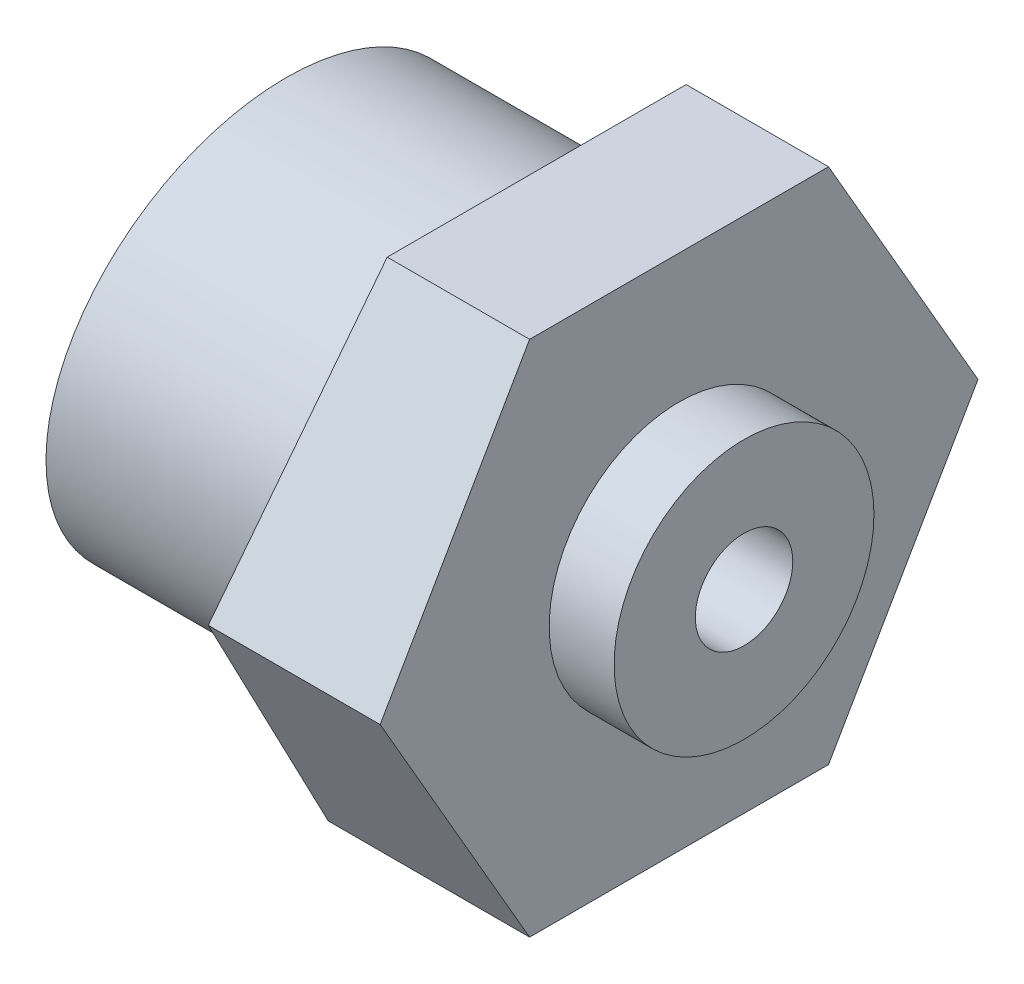
SolidWorks part; units mm, degrees
ref_plane "Front Plane" through (0, 0, 0) normal (0, 0, 1) x (1, 0, 0)
ref_plane "Top Plane" through (0, 0, 0) normal (0, 1, 0) x (1, 0, 0)
ref_plane "Right Plane" through (0, 0, 0) normal (1, 0, 0) x (0, 0, -1)
sketch "Croquis1" plane through (0, 0, 0) normal (1, 0, 0) x (0, 0, -1)
  line L1 (-4.6015, 0) -> (-2.3007, -3.985)
  line L2 (-2.3007, -3.985) -> (2.3007, -3.985)
  line L3 (2.3007, -3.985) -> (4.6015, 0)
  line L4 (4.6015, 0) -> (2.3007, 3.985)
  line L5 (2.3007, 3.985) -> (-2.3007, 3.985)
  line L6 (-2.3007, 3.985) -> (-4.6015, 0)
  circle A0 centre (0, 0) radius 3.985 construction
  dimension "D1" = 7.97
extrude "Saliente-Extruir1" add sketch "Croquis1" against normal blind 3.1
sketch "Croquis2" plane through (0, 0, 0) normal (0, 0, 1) x (1, 0, 0)
  line L0 (-3.1, -3.985) -> (-2.1919, 3.985)
  line L1 (-3.1, 3.985) -> (0, 3.985) construction
  line L2 (-2.1919, 3.985) -> (-3.5279, 3.985)
  line L3 (-3.5279, 3.985) -> (-3.1, -3.985)
  dimension "D1" = 83.5
extrude "Cortar-Extruir1" cut sketch "Croquis2" against normal mid plane 33
sketch "Croquis3" plane through (0, 0, 0) normal (1, 0, 0) x (0, 0, -1)
  circle A0 centre (0, 0) radius 3.3
  dimension "D1" = 6.6
extrude "Saliente-Extruir2" add sketch "Croquis3" against normal blind 6.8
sketch "Croquis4" plane through (0, 0, 0) normal (0, 0, 1) x (1, 0, 0)
  line L0 (-6.8, -3.3) -> (-6.048, 3.3)
  line L1 (-2.27, 3.3) -> (-6.8, 3.3) construction
  line L2 (-6.048, 3.3) -> (-6.8, 3.3)
  line L3 (-6.8, 3.3) -> (-6.8, -3.3)
  dimension "D1" = 83.5
extrude "Cortar-Extruir2" cut sketch "Croquis4" against normal mid plane 6.8
sketch "Croquis5" plane through (0, 0, 0) normal (1, 0, 0) x (0, 0, -1)
  circle A0 centre (0, 0) radius 2
  dimension "D1" = 4
extrude "Saliente-Extruir3" add sketch "Croquis5" along normal blind 1
sketch "Croquis6" plane through (1, 0, 0) normal (1, 0, 0) x (0, 0, -1)
  circle A0 centre (0, 0) radius 0.75
  dimension "D1" = 1.5
extrude "Cortar-Extruir3" cut sketch "Croquis6" against normal through all
